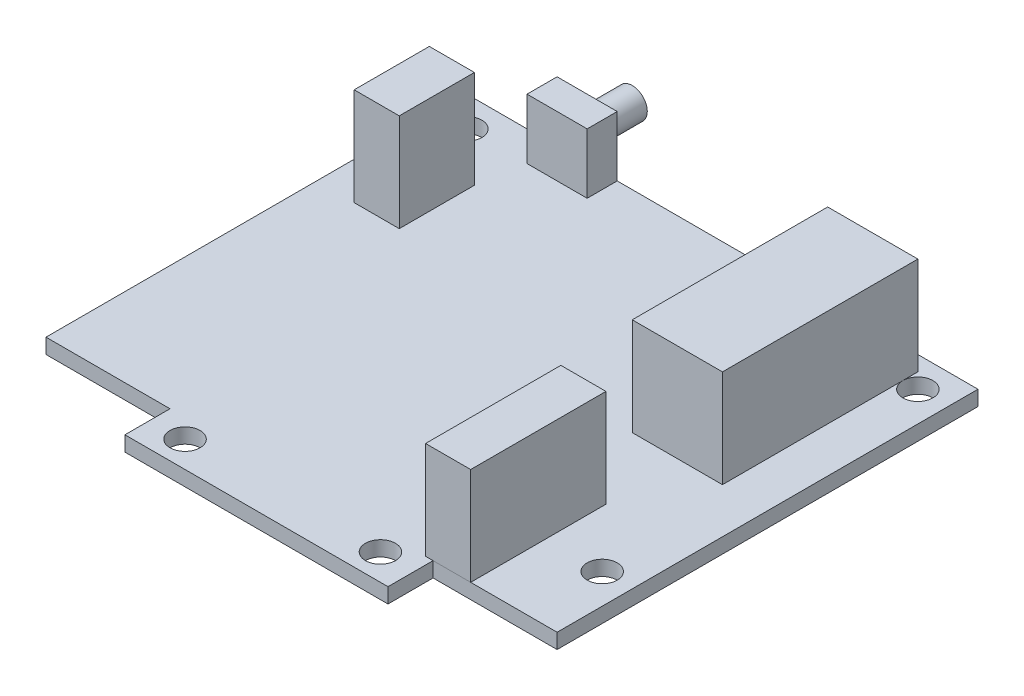
SolidWorks part; units mm, degrees
ref_plane "Front Plane" through (0, 0, 0) normal (0, 0, 1) x (1, 0, 0)
ref_plane "Top Plane" through (0, 0, 0) normal (0, 1, 0) x (1, 0, 0)
ref_plane "Right Plane" through (0, 0, 0) normal (1, 0, 0) x (0, 0, -1)
sketch "Sketch1" plane through (0, 0, 0) normal (0, 1, 0) x (1, 0, 0)
  line L0 (13.8906, -22.225) -> (26.9875, -22.225)
  line L1 (-26.9875, 22.225) -> (26.9875, 22.225)
  line L2 (-26.9875, 22.225) -> (-26.9875, -22.225)
  line L3 (-26.9875, -22.225) -> (-13.8906, -22.225)
  line L4 (26.9875, 22.225) -> (26.9875, -22.225)
  line L5 (-26.9875, 22.225) -> (26.9875, -22.225) construction
  line L6 (-26.9875, -22.225) -> (26.9875, 22.225) construction
  line L8 (-13.8906, -22.225) -> (-13.8906, -26.9875)
  line L9 (-13.8906, -26.9875) -> (13.8906, -26.9875)
  line L10 (13.8906, -22.225) -> (13.8906, -26.9875)
  point P0 (0, 0)
  point P10 (0, -26.9875)
  dimension "D1" = 53.975
  dimension "D2" = 44.45
  dimension "D3" = 27.7812
  dimension "D4" = 4.7625
extrude "Boss-Extrude1" add sketch "Sketch1" along normal blind 1.5875
sketch "Sketch2" plane through (0, 1.5875, 0) normal (0, 1, 0) x (1, 0, 0)
  line L0 (13.8906, -22.225) -> (26.9875, -22.225) construction
  line L1 (13.0969, -22.225) -> (17.8594, -22.225)
  line L2 (13.0969, -22.225) -> (13.0969, -7.9375)
  line L3 (13.0969, -7.9375) -> (17.8594, -7.9375)
  line L4 (17.8594, -22.225) -> (17.8594, -7.9375)
  line L5 (13.8906, -26.9875) -> (13.8906, -22.225) construction
  line L6 (-26.9875, 22.225) -> (-26.9875, -22.225) construction
  line L7 (-23.0188, 14.2875) -> (-18.2563, 14.2875)
  line L8 (-23.0188, 14.2875) -> (-23.0188, 6.35)
  line L9 (-23.0188, 6.35) -> (-18.2563, 6.35)
  line L10 (-18.2563, 14.2875) -> (-18.2563, 6.35)
  line L11 (26.9875, 22.225) -> (-26.9875, 22.225) construction
  line L12 (26.9875, -22.225) -> (26.9875, 22.225) construction
  line L13 (-17.4625, 22.225) -> (-11.1125, 22.225)
  line L14 (-17.4625, 22.225) -> (-17.4625, 19.05)
  line L15 (-17.4625, 19.05) -> (-11.1125, 19.05)
  line L16 (-11.1125, 22.225) -> (-11.1125, 19.05)
  line L17 (12.7, 20.6375) -> (22.225, 20.6375)
  line L18 (12.7, 20.6375) -> (12.7, 0)
  line L19 (12.7, 0) -> (22.225, 0)
  line L20 (22.225, 20.6375) -> (22.225, 0)
  dimension "D1" = 14.2875
  dimension "D2" = 4.7625
  dimension "D3" = 0.7937
  dimension "D4" = 3.9688
  dimension "D5" = 4.7625
  dimension "D6" = 7.9375
  dimension "D7" = 7.9375
  dimension "D8" = 9.525
  dimension "D9" = 6.35
  dimension "D10" = 3.175
  dimension "D11" = 9.525
  dimension "D12" = 20.6375
  dimension "D13" = 1.5875
  dimension "D14" = 4.7625
extrude "Boss-Extrude2" add sketch "Sketch2" along normal blind 10.3187 separate body
sketch "Sketch3" plane through (0, 0, -22.225) normal (0, 0, -1) x (-1, 0, 0)
  line L0 (11.1125, 11.9062) -> (17.4625, 11.9062) construction
  line L1 (11.1125, 11.9062) -> (11.1125, 1.5875) construction
  line L2 (17.4625, 1.5875) -> (11.1125, 1.5875) construction
  line L3 (17.4625, 1.5875) -> (17.4625, 7.9375) construction
  line L4 (17.4625, 7.9375) -> (11.1125, 7.9375) construction
  line L5 (11.1125, 1.5875) -> (11.1125, 7.9375) construction
  line L6 (-26.9875, 1.5875) -> (26.9875, 1.5875) construction
  line L7 (17.4625, 11.9062) -> (17.4625, 1.5875) construction
  circle A0 centre (14.2875, 4.7625) radius 1.5875
  point P4 (14.2875, 11.9062)
  point P14 (17.4625, 4.7625)
  dimension "D2" = 3.175
  dimension "D1" = 6.35
extrude "Boss-Extrude3" add sketch "Sketch3" along normal blind 4.7625
sketch "Sketch4" plane through (0, 0, -22.225) normal (0, 0, -1) x (-1, 0, 0)
  line L0 (11.1125, 11.9062) -> (11.1125, 1.5875) construction
  line L1 (17.4625, 11.9062) -> (11.1125, 11.9062)
  line L2 (17.4625, 11.9062) -> (17.4625, 7.9375)
  line L3 (17.4625, 7.9375) -> (11.1125, 7.9375)
  line L4 (11.1125, 11.9062) -> (11.1125, 7.9375)
  line L5 (-26.9875, 1.5875) -> (26.9875, 1.5875) construction
  dimension "D1" = 6.35
extrude "Cut-Extrude1" cut sketch "Sketch4" against normal through all
sketch "Sketch5" plane through (0, 0, 0) normal (0, -1, 0) x (1, 0, 0)
  line L0 (26.9875, -22.225) -> (-26.9875, -22.225) construction
  line L1 (8.7312, -20.6375) -> (-8.7312, -20.6375)
  line L2 (8.7312, -20.6375) -> (8.7313, -13.8906)
  line L3 (8.7312, -3.175) -> (-8.7312, -3.175)
  line L4 (-8.7312, -20.6375) -> (-8.7313, -13.8906)
  line L5 (-8.7313, -13.8906) -> (-10.3188, -13.8906)
  line L6 (-8.7313, -9.9219) -> (-10.3188, -9.9219)
  line L7 (0, -20.6375) -> (0, -3.175) construction
  line L8 (-8.7313, -9.9219) -> (-8.7312, -3.175)
  line L9 (8.7313, -9.9219) -> (10.3188, -9.9219)
  line L10 (8.7313, -13.8906) -> (10.3188, -13.8906)
  line L11 (8.7313, -9.9219) -> (8.7312, -3.175)
  arc A0 (-10.3188, -13.8906) -> (-10.3188, -9.9219) centre (-10.3188, -11.9063) cw
  arc A1 (10.3188, -13.8906) -> (10.3188, -9.9219) centre (10.3188, -11.9063) ccw
  point P5 (0, -3.175)
  point P17 (0, -11.9063)
  dimension "D4" = 1.9844
  dimension "D1" = 17.4625
  dimension "D2" = 1.5875
  dimension "D3" = 1.5875
  dimension "D5" = 17.4625
extrude "Boss-Extrude4" add sketch "Sketch5" along normal blind 7.9375
sketch "Sketch6" plane through (0, -7.9375, 0) normal (0, -1, 0) x (1, 0, 0)
  line L0 (-8.7312, -20.6375) -> (8.7312, -20.6375) construction
  line L2 (1.1906, -20.6375) -> (-1.1906, -20.6375)
  line L3 (1.1906, -20.6375) -> (1.1906, -19.7539)
  line L5 (-1.1906, -20.6375) -> (-1.1906, -19.7539)
  arc A0 (1.1906, -19.7539) -> (-1.1906, -19.7539) centre (0, -11.9063) ccw
  arc A1 (10.3188, -13.8906) -> (10.3188, -9.9219) centre (10.3188, -11.9063) ccw construction
  point P6 (12.3031, -11.9063)
  point P10 (0, -20.6375)
  point P15 (0, -20.6375)
  dimension "D1" = 15.875
  dimension "D2" = 2.3813
extrude "Boss-Extrude5" add sketch "Sketch6" along normal blind 6.35
sketch "Sketch7" plane through (0, 0, 0) normal (0, -1, 0) x (1, 0, 0)
  line L0 (-26.9875, -22.225) -> (-26.9875, 22.225) construction
  line L1 (26.9875, 22.225) -> (26.9875, -22.225) construction
  line L2 (26.9875, -22.225) -> (-26.9875, -22.225) construction
  line L3 (13.8906, 22.225) -> (26.9875, 22.225) construction
  line L4 (13.8906, 26.9875) -> (13.8906, 22.225) construction
  line L5 (-13.8906, 22.225) -> (-13.8906, 26.9875) construction
  line L6 (-13.8906, 26.9875) -> (13.8906, 26.9875) construction
  circle A0 centre (23.8125, -19.05) radius 1.5875
  circle A2 centre (-23.8125, -19.05) radius 1.5875
  circle A3 centre (-10.3187, 24.2094) radius 1.5875
  circle A4 centre (10.3187, 24.2094) radius 1.5875
  circle A5 centre (23.8125, 14.2875) radius 1.5875
  dimension "D8" = 3.175
  dimension "D1" = 3.175
  dimension "D2" = 3.175
  dimension "D3" = 3.175
  dimension "D4" = 7.9375
  dimension "D5" = 3.5719
  dimension "D6" = 3.5719
  dimension "D7" = 2.7781
extrude "Cut-Extrude2" cut sketch "Sketch7" against normal through all
sketch "Sketch8" plane through (0, 1.5875, 0) normal (0, 1, 0) x (1, 0, 0)
  line L0 (-26.9875, -2.6827) -> (26.9875, -2.6827) construction
  line L1 (-26.9875, 22.225) -> (-26.9875, -22.225) construction
  line L2 (26.9875, -22.225) -> (26.9875, 22.225) construction
  text T0 "Pixy"
sketch "Sketch9" plane through (0, 0, 0) normal (0, -1, 0) x (1, 0, 0)
  line L0 (-13.8906, 26.9875) -> (13.8906, 26.9875) construction
  line L1 (1.5875, 22.225) -> (-1.5875, 22.225)
  line L2 (1.5875, 22.225) -> (1.5875, 24.6062)
  line L3 (1.5875, 24.6062) -> (-1.5875, 24.6062)
  line L4 (-1.5875, 22.225) -> (-1.5875, 24.6062)
  line L5 (13.8906, 22.225) -> (26.9875, 22.225) construction
  point P6 (0, 24.6062)
  point P7 (0, 26.9875)
  dimension "D1" = 3.175
  dimension "D2" = 2.3813
extrude "Boss-Extrude6" add sketch "Sketch9" along normal blind 1.5875
